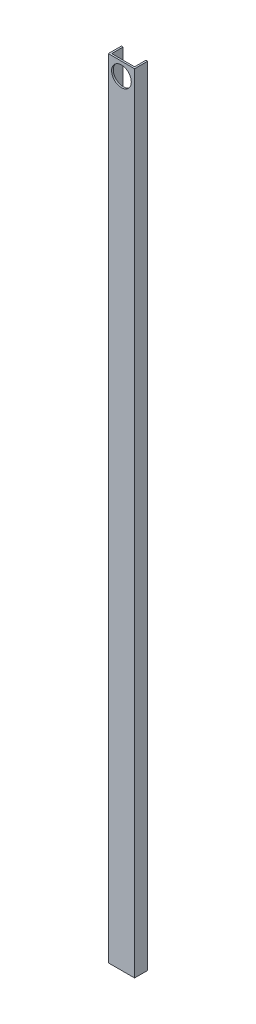
SolidWorks part; units mm, degrees
ref_plane "Front Plane" through (0, 0, 0) normal (0, 0, 1) x (1, 0, 0)
ref_plane "Top Plane" through (0, 0, 0) normal (0, 1, 0) x (1, 0, 0)
ref_plane "Right Plane" through (0, 0, 0) normal (1, 0, 0) x (0, 0, -1)
sketch "Sketch1" plane through (0, 0, 0) normal (0, 1, 0) x (1, 0, 0)
  line L0 (0, 0) -> (50.8, 0)
  line L1 (50.8, 0) -> (50.8, 25.4)
  line L2 (50.8, 25.4) -> (47.498, 25.4)
  line L3 (47.498, 25.4) -> (47.498, 3.302)
  line L4 (47.498, 3.302) -> (3.302, 3.302)
  line L5 (3.302, 3.302) -> (3.302, 25.4)
  line L6 (3.302, 25.4) -> (0, 25.4)
  line L7 (0, 25.4) -> (0, 0)
  line L8 (0, 0) -> (2.3496, 0.3916)
  dimension "D1" = 25.4
  dimension "D2" = 25.4
  dimension "D3" = 50.8
  dimension "D4" = 3.302
  dimension "D5" = 3.302
  dimension "D6" = 3.302
extrude "Boss-Extrude1" add sketch "Sketch1" along normal blind 1524 contours L0 L1 L2 L3 L4 L5 L6 L7
sketch "Sketch2" plane through (0, 0, 0) normal (0, 0, 1) x (1, 0, 0)
  line L0 (0, 1524) -> (50.8, 1524) construction
  line L1 (50.8, 1524) -> (50.8, 0) construction
  circle A0 centre (25.4, 1498.6) radius 19.05
  dimension "D1" = 25.4
  dimension "D2" = 25.4
extrude "Cut-Extrude1" cut sketch "Sketch2" against normal blind 3.302 contours A0
